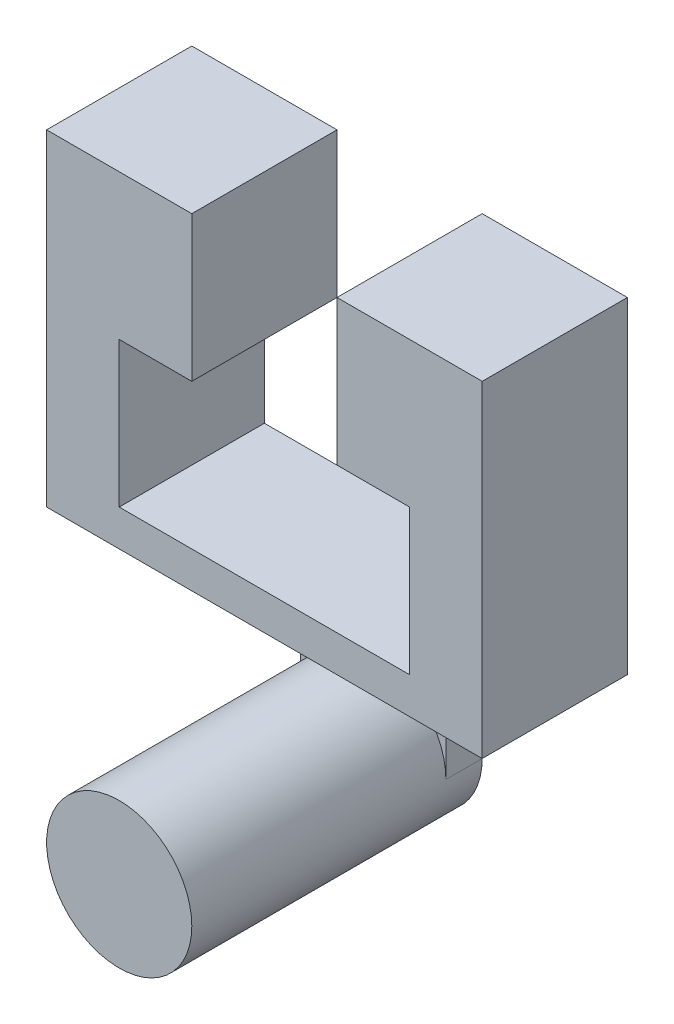
SolidWorks part; units mm, degrees
material "ASTM A36 Steel"
ref_plane "Front Plane" through (0, 0, 0) normal (0, 0, 1) x (1, 0, 0)
ref_plane "Top Plane" through (0, 0, 0) normal (0, 1, 0) x (1, 0, 0)
ref_plane "Right Plane" through (0, 0, 0) normal (1, 0, 0) x (0, 0, -1)
sketch "Sketch1" plane through (0, 0, 0) normal (0, 0, 1) x (1, 0, 0)
  line L0 (-12.7, 0) -> (-12.7, 25.4)
  line L1 (-12.7, 25.4) -> (12.7, 25.4)
  line L2 (12.7, 25.4) -> (12.7, 0)
  arc A0 (12.7, 0) -> (-12.7, 0) centre (0, 0) ccw
  arc A1 (12.7, 0) -> (-12.7, 0) centre (0, 0) ccw
  dimension "D1" = 25.4
  dimension "D2" = 25.4
extrude "Boss-Extrude1" add sketch "Sketch1" along normal blind 6.35 contours A1 L0 L1 L2
sketch "Sketch2" plane through (0, 0, 0) normal (0, 0, 1) x (1, 0, 0)
  circle A0 centre (0, 0) radius 12.7
  dimension "D1" = 25.4
extrude "Boss-Extrude2" add sketch "Sketch2" along normal blind 50.8
sketch "Sketch3" plane through (0, 0, 0) normal (0, 0, 1) x (1, 0, 0)
  line L0 (-38.1, 25.4) -> (38.1, 25.4)
  line L1 (38.1, 25.4) -> (38.1, 82.55)
  line L2 (38.1, 82.55) -> (-38.1, 82.55)
  line L3 (-38.1, 82.55) -> (-38.1, 25.4)
  point P3 (0, 25.4)
  dimension "D1" = 76.2
  dimension "D2" = 57.15
extrude "Boss-Extrude3" add sketch "Sketch3" along normal blind 25.4
sketch "Sketch4" plane through (0, 0, 25.4) normal (0, 0, 1) x (1, 0, 0)
  line L0 (12.7, 82.55) -> (12.7, 57.15)
  line L1 (38.1, 82.55) -> (-38.1, 82.55) construction
  line L2 (12.7, 57.15) -> (25.4, 57.15)
  line L3 (25.4, 57.15) -> (25.4, 31.75)
  line L4 (25.4, 31.75) -> (-25.4, 31.75)
  line L5 (-25.4, 31.75) -> (-25.4, 57.15)
  line L6 (-25.4, 57.15) -> (-12.7, 57.15)
  line L7 (-12.7, 57.15) -> (-12.7, 82.55)
  line L8 (-12.7, 82.55) -> (12.7, 82.55)
  line L9 (38.1, 25.4) -> (38.1, 82.55) construction
  line L10 (-38.1, 82.55) -> (-38.1, 25.4) construction
  line L11 (-38.1, 25.4) -> (38.1, 25.4) construction
  dimension "D1" = 25.4
  dimension "D2" = 12.7
  dimension "D3" = 12.7
  dimension "D4" = 25.4
  dimension "D5" = 6.35
  dimension "D6" = 25.4
  dimension "D7" = 25.4
extrude "Cut-Extrude1" cut sketch "Sketch4" against normal through all contours L8 L0 L2 L3 L4 L5 L6 L7
